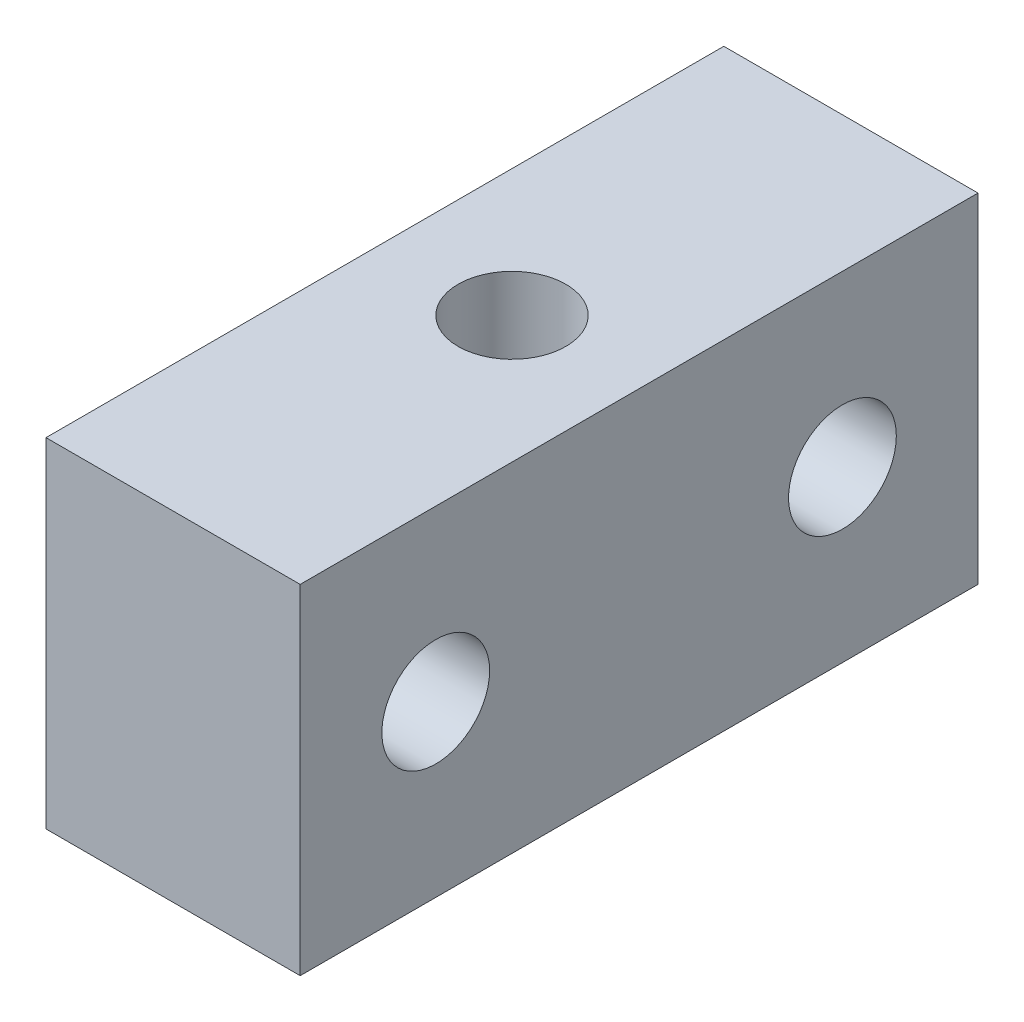
SolidWorks part; units mm, degrees
material "6061-T6 (SS)"
ref_plane "Front Plane" through (0, 0, 0) normal (0, 0, 1) x (1, 0, 0)
ref_plane "Top Plane" through (0, 0, 0) normal (0, 1, 0) x (1, 0, 0)
ref_plane "Right Plane" through (0, 0, 0) normal (1, 0, 0) x (0, 0, -1)
sketch "Sketch1" plane through (0, 0, 0) normal (1, 0, 0) x (0, 0, -1)
  line L0 (-12.7, 6.35) -> (-12.7, -6.35)
  line L1 (-12.7, 6.35) -> (12.7, 6.35)
  line L2 (-12.7, -6.35) -> (12.7, -6.35)
  line L3 (12.7, 6.35) -> (12.7, -6.35)
  line L4 (12.7, 6.35) -> (-12.7, -6.35) construction
  line L5 (2.54, 0) -> (-2.54, 0) construction
  line L6 (-5.08, 0) -> (-10.16, 0) construction
  circle A0 centre (-7.62, 0) radius 2.54 construction
  dimension "D4" = 2.54
  dimension "D1" = 12.7
  dimension "D2" = 2.54
  dimension "D3" = 5.08
extrude "Boss-Extrude1" add sketch "Sketch1" along normal mid plane 9.525
hole_wizard "#10-32 Tapped Hole1" positions "Sketch2" profile "Sketch3" tap size "#10-32" standard "ANSI Inch" end condition through all
sketch "Sketch2" plane through (0, 6.35, 0) normal (0, 1, 0) x (1, 0, 0)
  point P0 (0, 0)
sketch "Sketch3" plane through (0, 6.35, 0) normal (1, 0, 0) x (0, 0, 1)
  line L0 (0, 0) -> (0, 12.7)
  line L1 (0, 12.7) -> (2.0193, 12.7)
  line L2 (2.0193, 12.7) -> (2.0193, 0)
  line L5 (2.0193, 0) -> (0, 0)
  line L11 (0, -6.35) -> (0, 107.95) construction
  dimension "Thru Tap Drill Dia." = 4.0386
  dimension "Thru Tap Drill Depth" = 12.7
cosmetic thread "Hole Thread1" parameters "D2"=4.826
hole_wizard "#10-32 Tapped Hole2" positions "Sketch5" profile "Sketch4" tap size "#10-32" standard "ANSI Inch" end condition through all
sketch "Sketch5" plane through (4.7625, 0, 0) normal (1, 0, 0) x (0, 0, -1)
  line L0 (-7.62, 0) -> (7.62, 0) construction
  point P0 (-7.62, 0)
  point P10 (7.62, 0)
sketch "Sketch4" plane through (4.7625, 0, 7.62) normal (0, 1, 0) x (0, 0, -1)
  line L0 (0, 0) -> (0, 9.525)
  line L1 (0, 9.525) -> (2.0193, 9.525)
  line L2 (2.0193, 9.525) -> (2.0193, 0)
  line L5 (2.0193, 0) -> (0, 0)
  line L11 (0, -6.35) -> (0, 107.95) construction
  dimension "Thru Tap Drill Dia." = 4.0386
  dimension "Thru Tap Drill Depth" = 9.525
cosmetic thread "Hole Thread2" parameters "D2"=4.826
cosmetic thread "Hole Thread3" parameters "D2"=4.826
